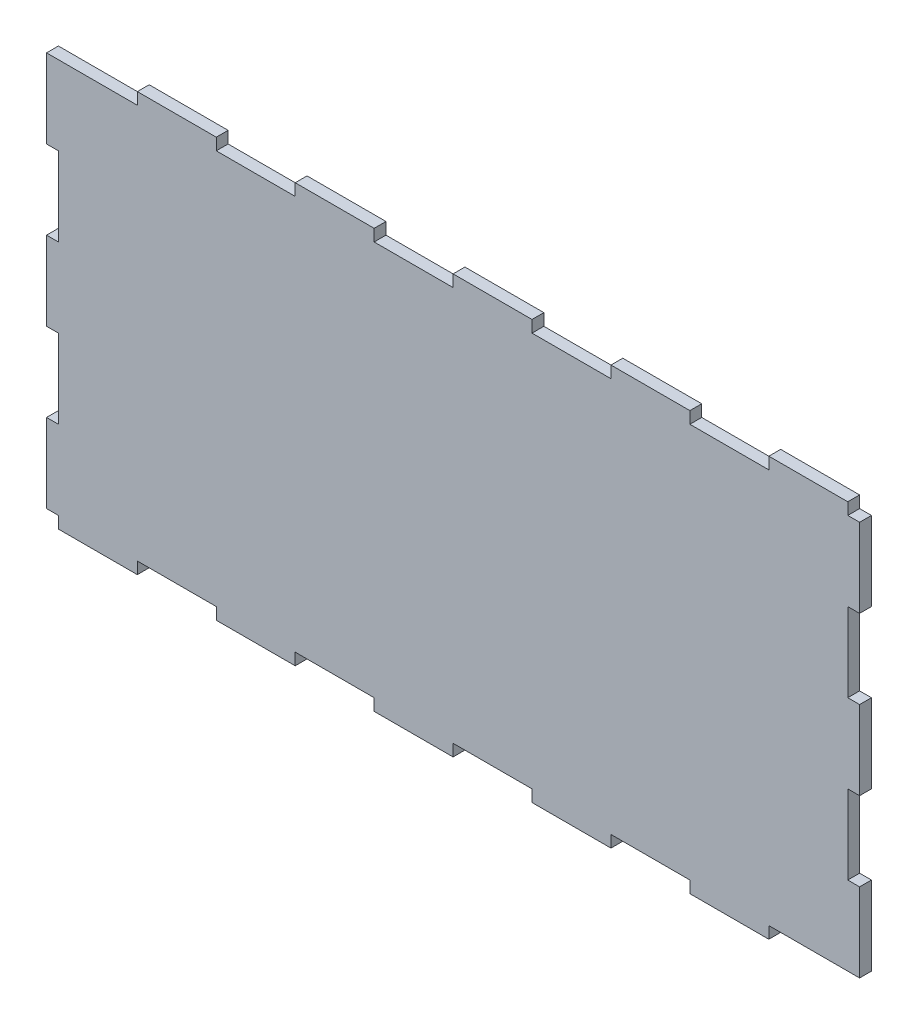
SolidWorks part; units mm, degrees
ref_plane "Front Plane" through (0, 0, 0) normal (0, 0, 1) x (1, 0, 0)
ref_plane "Top Plane" through (0, 0, 0) normal (0, 1, 0) x (1, 0, 0)
ref_plane "Right Plane" through (0, 0, 0) normal (1, 0, 0) x (0, 0, -1)
sketch "Sketch1" plane through (0, 0, 0) normal (0, 0, 1) x (1, 0, 0)
  line L0 (70.1904, 52.7436) -> (70.1904, 55.7436)
  line L1 (-89.8096, 52.7436) -> (-69.8096, 52.7436)
  line L2 (-89.8096, 32.7436) -> (-89.8096, 12.7436)
  line L3 (-69.8096, -47.2564) -> (-49.8096, -47.2564)
  line L4 (110.1904, 32.7436) -> (110.1904, 12.7436)
  line L5 (70.1904, 52.7436) -> (90.1904, 52.7436)
  line L6 (110.1904, 52.7436) -> (110.1904, 55.7436)
  line L7 (110.1904, 55.7436) -> (90.1904, 55.7436)
  line L8 (90.1904, 52.7436) -> (90.1904, 55.7436)
  line L9 (70.1904, 55.7436) -> (50.1904, 55.7436)
  line L10 (50.1904, 52.7436) -> (50.1904, 55.7436)
  line L11 (30.1904, 52.7436) -> (30.1904, 55.7436)
  line L12 (30.1904, 55.7436) -> (10.1904, 55.7436)
  line L13 (10.1904, 52.7436) -> (10.1904, 55.7436)
  line L14 (-9.8096, 52.7436) -> (-9.8096, 55.7436)
  line L15 (-9.8096, 55.7436) -> (-29.8096, 55.7436)
  line L16 (-29.8096, 52.7436) -> (-29.8096, 55.7436)
  line L17 (-49.8096, 52.7436) -> (-49.8096, 55.7436)
  line L18 (-49.8096, 55.7436) -> (-69.8096, 55.7436)
  line L19 (-69.8096, 52.7436) -> (-69.8096, 55.7436)
  line L20 (30.1904, 52.7436) -> (50.1904, 52.7436)
  line L21 (-9.8096, 52.7436) -> (10.1904, 52.7436)
  line L22 (-49.8096, 52.7436) -> (-29.8096, 52.7436)
  line L23 (110.1904, 12.7436) -> (113.1904, 12.7436)
  line L24 (110.1904, 52.7436) -> (113.1904, 52.7436)
  line L25 (110.1904, -7.2564) -> (110.1904, -27.2564)
  line L26 (110.1904, 32.7436) -> (113.1904, 32.7436)
  line L27 (113.1904, 52.7436) -> (113.1904, 32.7436)
  line L28 (113.1904, 12.7436) -> (113.1904, -7.2564)
  line L29 (110.1904, -7.2564) -> (113.1904, -7.2564)
  line L30 (110.1904, -27.2564) -> (113.1904, -27.2564)
  line L31 (113.1904, -27.2564) -> (113.1904, -47.2564)
  line L32 (110.1904, -47.2564) -> (113.1904, -47.2564)
  line L33 (-49.8096, -47.2564) -> (-49.8096, -50.2564)
  line L34 (-29.8096, -47.2564) -> (-9.8096, -47.2564)
  line L35 (-89.8096, -47.2564) -> (-89.8096, -50.2564)
  line L36 (-89.8096, -50.2564) -> (-69.8096, -50.2564)
  line L37 (-69.8096, -47.2564) -> (-69.8096, -50.2564)
  line L38 (-49.8096, -50.2564) -> (-29.8096, -50.2564)
  line L39 (-29.8096, -47.2564) -> (-29.8096, -50.2564)
  line L40 (-9.8096, -47.2564) -> (-9.8096, -50.2564)
  line L41 (-9.8096, -50.2564) -> (10.1904, -50.2564)
  line L42 (10.1904, -47.2564) -> (10.1904, -50.2564)
  line L43 (30.1904, -47.2564) -> (30.1904, -50.2564)
  line L44 (30.1904, -50.2564) -> (50.1904, -50.2564)
  line L45 (50.1904, -47.2564) -> (50.1904, -50.2564)
  line L46 (70.1904, -47.2564) -> (70.1904, -50.2564)
  line L47 (70.1904, -50.2564) -> (90.1904, -50.2564)
  line L48 (90.1904, -47.2564) -> (90.1904, -50.2564)
  line L49 (10.1904, -47.2564) -> (30.1904, -47.2564)
  line L50 (50.1904, -47.2564) -> (70.1904, -47.2564)
  line L51 (90.1904, -47.2564) -> (110.1904, -47.2564)
  line L52 (-89.8096, 12.7436) -> (-92.8096, 12.7436)
  line L53 (-89.8096, -47.2564) -> (-92.8096, -47.2564)
  line L55 (-89.8096, -27.2564) -> (-92.8096, -27.2564)
  line L56 (-92.8096, -47.2564) -> (-92.8096, -27.2564)
  line L57 (-92.8096, -7.2564) -> (-92.8096, 12.7436)
  line L58 (-89.8096, -7.2564) -> (-92.8096, -7.2564)
  line L59 (-89.8096, 52.7436) -> (-92.8096, 52.7436)
  line L60 (-92.8096, 32.7436) -> (-92.8096, 52.7436)
  line L61 (-89.8096, 32.7436) -> (-92.8096, 32.7436)
  line L62 (-89.8096, -7.2564) -> (-89.8096, -27.2564)
extrude "Boss-Extrude1" add sketch "Sketch1" along normal blind 3
